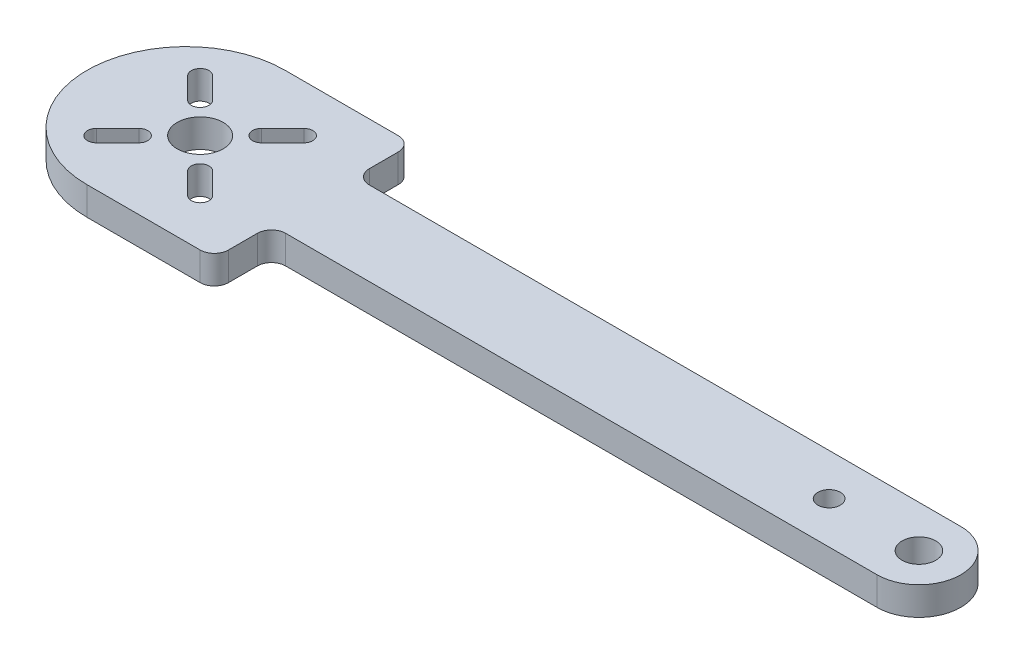
SolidWorks part; units mm, degrees
material "Thornel VCB-20 Carbon Cloth"
ref_plane "Front Plane" through (0, 0, 0) normal (0, 0, 1) x (1, 0, 0)
ref_plane "Top Plane" through (0, 0, 0) normal (0, 1, 0) x (1, 0, 0)
ref_plane "Right Plane" through (0, 0, 0) normal (1, 0, 0) x (0, 0, -1)
sketch "Sketch1" plane through (0, 0, 0) normal (0, 1, 0) x (1, 0, 0)
  line L0 (-58.0134, 7.2134) -> (-43.5866, -7.2134) construction
  line L1 (-50.8, 14) -> (-36.8, 14)
  line L2 (-50.8, 14) -> (-50.8, -14) construction
  line L3 (-50.8, -14) -> (-36.8, -14)
  line L7 (-58.4887, -7.6887) -> (-43.1113, 7.6887) construction
  line L8 (-58.1362, 7.3362) -> (-55.131, 4.331) construction
  line L9 (-57.2523, 8.2201) -> (-54.2471, 5.2149)
  line L10 (-59.0201, 6.4523) -> (-56.0149, 3.4471)
  line L11 (-43.4638, 7.3362) -> (-46.469, 4.331) construction
  line L12 (-42.5799, 6.4523) -> (-45.5851, 3.4471)
  line L13 (-44.3477, 8.2201) -> (-47.3529, 5.2149)
  line L14 (-43.4638, -7.3362) -> (-46.469, -4.331) construction
  line L15 (-44.3477, -8.2201) -> (-47.3529, -5.2149)
  line L16 (-42.5799, -6.4523) -> (-45.5851, -3.4471)
  line L17 (-58.1362, -7.3362) -> (-55.131, -4.331) construction
  line L18 (-59.0201, -6.4523) -> (-56.0149, -3.4471)
  line L19 (-57.2523, -8.2201) -> (-54.2471, -5.2149)
  line L21 (-34.8, 7.9146) -> (-34.8, 12)
  line L24 (-34.8, -12) -> (-34.8, -7.9146)
  line L32 (-32.8, 5.9146) -> (50.8, 5.9146)
  line L33 (-32.8, -5.9146) -> (50.8, -5.9146)
  line L34 (-50.8, 0) -> (50.8, 0) construction
  line L35 (-50.8, 14) -> (-52.8, 14)
  line L36 (-50.8, -14) -> (-52.8, -14)
  circle A2 centre (-50.8, 0) radius 3.25
  arc A3 (-57.2523, 8.2201) -> (-59.0201, 6.4523) centre (-58.1362, 7.3362) ccw
  arc A4 (-56.0149, 3.4471) -> (-54.2471, 5.2149) centre (-55.131, 4.331) ccw
  arc A5 (-42.5799, 6.4523) -> (-44.3477, 8.2201) centre (-43.4638, 7.3362) ccw
  arc A6 (-47.3529, 5.2149) -> (-45.5851, 3.4471) centre (-46.469, 4.331) ccw
  arc A7 (-44.3477, -8.2201) -> (-42.5799, -6.4523) centre (-43.4638, -7.3362) ccw
  arc A8 (-45.5851, -3.4471) -> (-47.3529, -5.2149) centre (-46.469, -4.331) ccw
  arc A9 (-59.0201, -6.4523) -> (-57.2523, -8.2201) centre (-58.1362, -7.3362) ccw
  arc A10 (-54.2471, -5.2149) -> (-56.0149, -3.4471) centre (-55.131, -4.331) ccw
  circle A11 centre (50.8, 0) radius 2.3813
  arc A12 (-34.8, -7.9146) -> (-32.8, -5.9146) centre (-32.8, -7.9146) cw
  arc A13 (-32.8, 5.9146) -> (-34.8, 7.9146) centre (-32.8, 7.9146) cw
  arc A14 (-36.8, -14) -> (-34.8, -12) centre (-36.8, -12) ccw
  arc A15 (-34.8, 12) -> (-36.8, 14) centre (-36.8, 12) ccw
  arc A16 (50.8, 5.9146) -> (50.8, -5.9146) centre (50.8, 0) cw
  arc A17 (-52.8, -14) -> (-52.8, 14) centre (-52.8, 0) cw
  point P0 (0, 0)
  point P12 (-50.8, 0)
  point P14 (-50.8, 0)
  point P17 (-56.6336, 5.8336)
  point P27 (-44.9664, 5.8336)
  point P34 (-44.9664, -5.8336)
  point P41 (-56.6336, -5.8336)
  point P46 (-50.8, 0)
  point P53 (-34.8, -7)
  point P56 (-34.8, 7)
  point P59 (-34.8, -14)
  point P62 (-34.8, 14)
  dimension "D3" = 6.5
  dimension "D6" = 8.25
  dimension "D10" = 4.7625
  dimension "D17" = 2
  dimension "D18" = 2
  dimension "D16" = 5.9146
  dimension "D2" = 14
  dimension "D4" = 45
  dimension "D5" = 45
  dimension "D7" = 4.25
  dimension "D8" = 2.5
  dimension "D11" = 16
  dimension "D12" = 16
  dimension "D13" = 7
  dimension "D14" = 7
  dimension "D15" = 101.6
  dimension "D19" = 50.8
  dimension "D20" = 2
  dimension "D9" = 4
extrude "Boss-Extrude1" add sketch "Sketch1" along normal blind 4
sketch "Sketch2" plane through (0, 0, 0) normal (0, -1, 0) x (1, 0, 0)
  circle A0 centre (38.1, 0) radius 1.5875
  circle A1 centre (50.8, 0) radius 2.3813 construction
  dimension "D1" = 3.175
  dimension "D2" = 12.7
extrude "Cut-Extrude1" cut sketch "Sketch2" against normal blind 10
